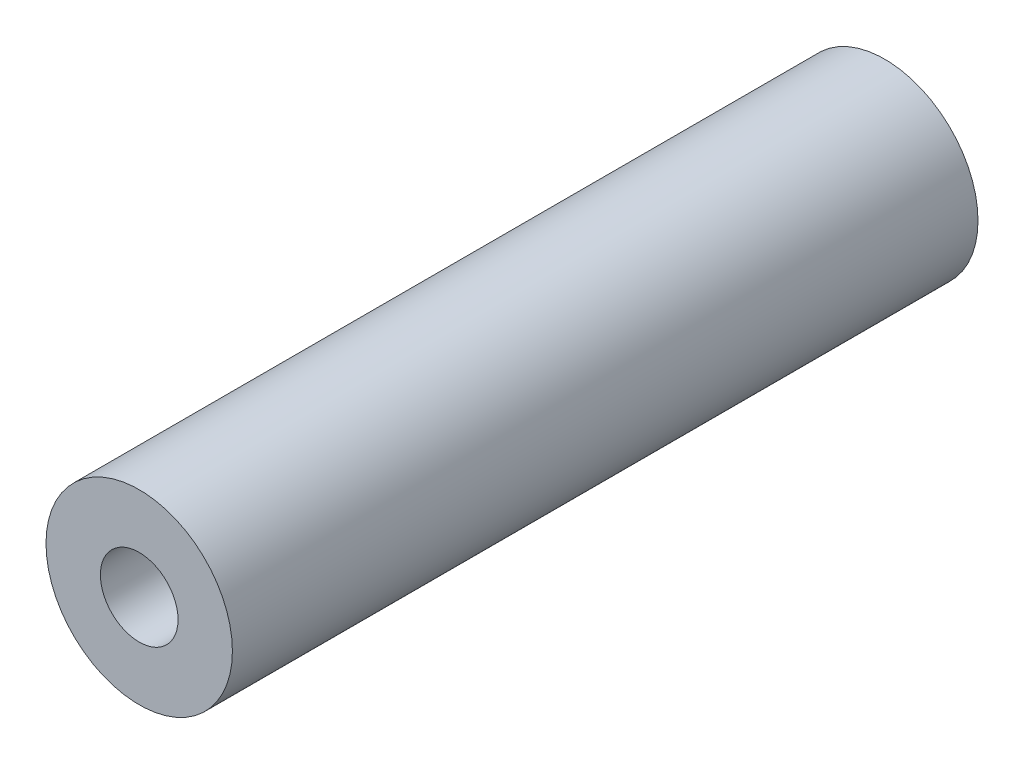
SolidWorks part; units mm, degrees
material "黄銅"
ref_plane "正面" through (0, 0, 0) normal (0, 0, 1) x (1, 0, 0)
ref_plane "平面" through (0, 0, 0) normal (0, 1, 0) x (1, 0, 0)
ref_plane "右側面" through (0, 0, 0) normal (1, 0, 0) x (0, 0, -1)
sketch "ｽｹｯﾁ1" plane through (0, 0, 0) normal (0, 0, 1) x (1, 0, 0)
  circle A0 centre (0, 0) radius 3
  dimension "D1" = 6
extrude "ﾎﾞｽ - 押し出し1" add sketch "ｽｹｯﾁ1" along normal mid plane 24
sketch "ｽｹｯﾁ2" plane through (0, 0, 12) normal (0, 0, 1) x (1, 0, 0)
  circle A0 centre (0, 0) radius 1.25
  dimension "D1" = 2.5
extrude "ｶｯﾄ - 押し出し1" cut sketch "ｽｹｯﾁ2" against normal blind 6
mirror "ﾐﾗｰ1" about plane through (0, 0, 0) normal (0, 0, 1) of "ｶｯﾄ - 押し出し1"
